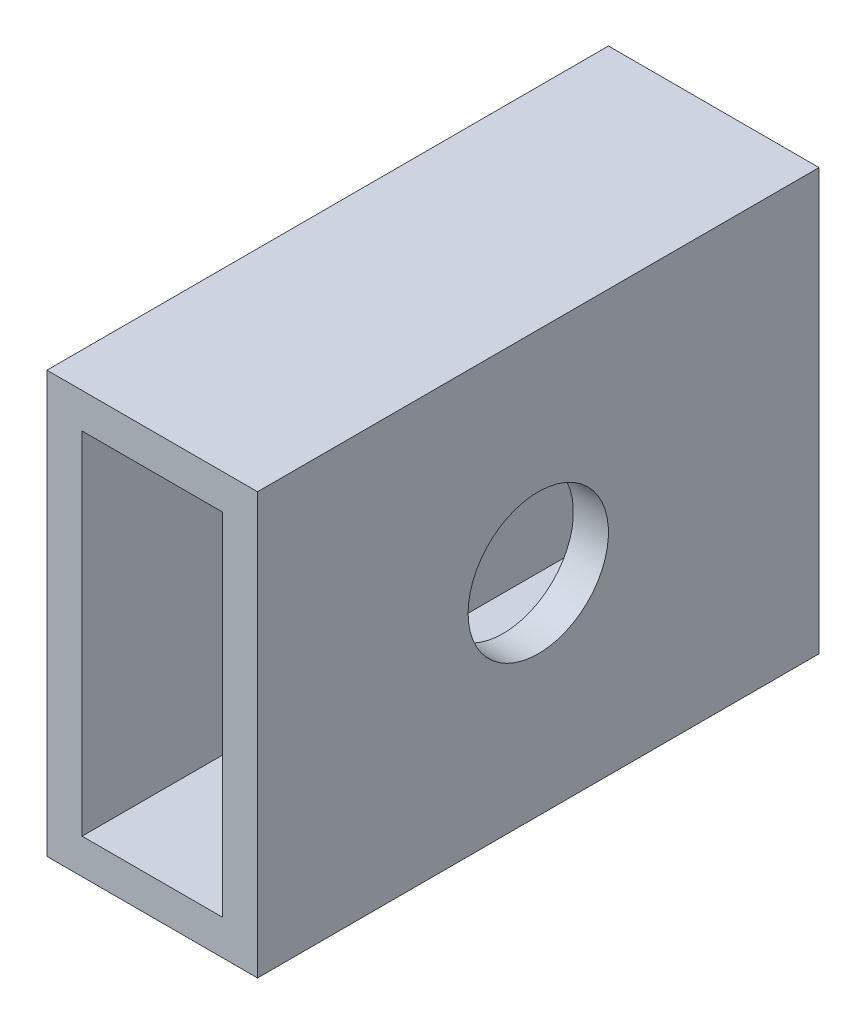
SolidWorks part; units mm, degrees
ref_plane "Front Plane" through (0, 0, 0) normal (0, 0, 1) x (1, 0, 0)
ref_plane "Top Plane" through (0, 0, 0) normal (0, 1, 0) x (1, 0, 0)
ref_plane "Right Plane" through (0, 0, 0) normal (1, 0, 0) x (0, 0, -1)
sketch "Sketch1" plane through (0, 0, 0) normal (0, 0, 1) x (1, 0, 0)
  line L1 (0, 0) -> (19.05, 0)
  line L2 (0, 0) -> (0, 38.1)
  line L3 (0, 38.1) -> (19.05, 38.1)
  line L4 (19.05, 0) -> (19.05, 38.1)
  dimension "D1" = 38.1
  dimension "D2" = 19.05
extrude "Extrude-Thin1" add sketch "Sketch1" along normal blind 50.8 thin thin type one direction reverse wall 3.175
sketch "Sketch3" plane through (0, 0, 0) normal (-1, 0, 0) x (0, 0, 1)
  line L2 (50.8, 38.1) -> (50.8, 0) construction
  line L3 (0, 19.05) -> (50.8, 19.05) construction
  line L5 (50.8, 38.1) -> (0, 38.1) construction
  line L6 (25.4, 38.1) -> (25.4, 0) construction
  line L7 (50.8, 0) -> (0, 0) construction
  line L8 (25.4, 38.1) -> (25.4, 0) construction
  line L9 (0, 38.1) -> (0, 0) construction
  circle A0 centre (25.4, 19.05) radius 6.35
  point P3 (0, 19.05)
  point P8 (25.4, 0)
  dimension "D1" = 12.7
extrude "Cut-Extrude2" cut sketch "Sketch3" against normal through all
sketch "Sketch4" plane through (0, 0, 0) normal (-1, 0, 0) x (0, 0, 1)
  point P3 (0, 19.05)
